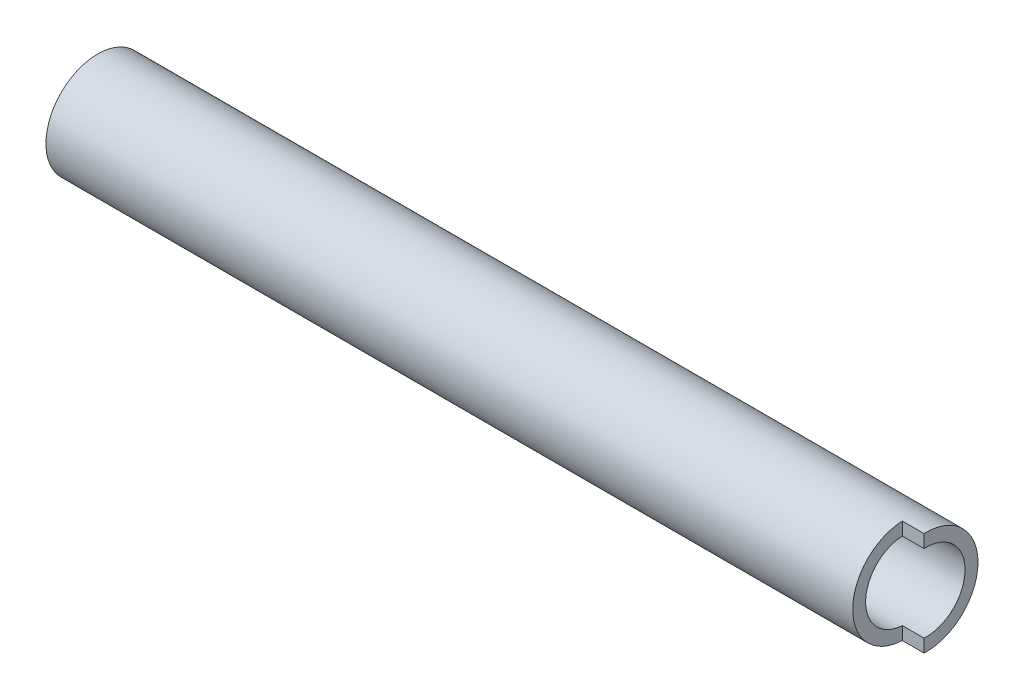
SolidWorks part; units mm, degrees
ref_plane "Front" through (0, 0, 0) normal (0, 0, 1) x (1, 0, 0)
ref_plane "Top" through (0, 0, 0) normal (0, 1, 0) x (1, 0, 0)
ref_plane "Right" through (0, 0, 0) normal (1, 0, 0) x (0, 0, -1)
sketch "Sketch1" plane through (0, 0, 0) normal (1, 0, 0) x (0, 0, -1)
  line L0 (3.5719, 0) -> (4.7625, 0) construction
  line L1 (3.5719, 0) -> (4.7625, 0) construction
  line L2 (4.1672, 0) -> (4.1672, 1.0672) construction
  circle A0 centre (0, 0) radius 4.7625
  circle A1 centre (0, 0) radius 3.5719
  point P4 (4.7625, 0)
  point P5 (3.5719, 0)
  dimension "OD" = 9.525
  dimension "ID" = 7.1437
  dimension "Wall Thickness" = 1.1906
sketch "Sketch2" plane through (0, 0, 0) normal (0, 0, 1) x (1, 0, 0)
  line L0 (-38.1, 0) -> (38.1, 0) construction
  point P2 (-26.1937, 0)
  point P3 (26.1937, 0)
  dimension "D1" = 11.9062
  dimension "D2" = 11.9062
sketch "Sketch3" plane through (0, 0, 0) normal (1, 0, 0) x (0, 0, -1)
  circle A0 centre (0, 0) radius 3.5719 construction
  circle A1 centre (0, 0) radius 4.7625 construction
  circle A2 centre (0, 0) radius 3.5719
  circle A3 centre (0, 0) radius 4.7625
extrude "Boss-Extrude1" add sketch "Sketch3" along normal mid plane 76.2
sketch "Sketch4" plane through (0, 0, 35) normal (0, 0, 1) x (1, 0, 0)
  line L0 (38.1, 23.6863) -> (38.1, -23.6863) construction
  line L1 (36.1, -5.7321) -> (40.1, -5.7321)
  line L2 (36.1, -5.7321) -> (36.1, 5.7321)
  line L3 (36.1, 5.7321) -> (40.1, 5.7321)
  line L4 (40.1, -5.7321) -> (40.1, 5.7321)
  line L5 (36.1, -5.7321) -> (40.1, 5.7321) construction
  line L6 (36.1, 5.7321) -> (40.1, -5.7321) construction
  point P0 (38.1, 0)
  point P5 (0, 0)
  dimension "D1" = 2
extrude "Cut-Extrude1" cut sketch "Sketch4" against normal blind 34.798
equation "\"D1@Boss-Extrude1\"=\"Length@Sketch2\""
equation "\"D1@Sketch2\"=\"OD@Sketch1\"*1.25"
equation "\"D2@Sketch2\"=\"D1@Sketch2\""
